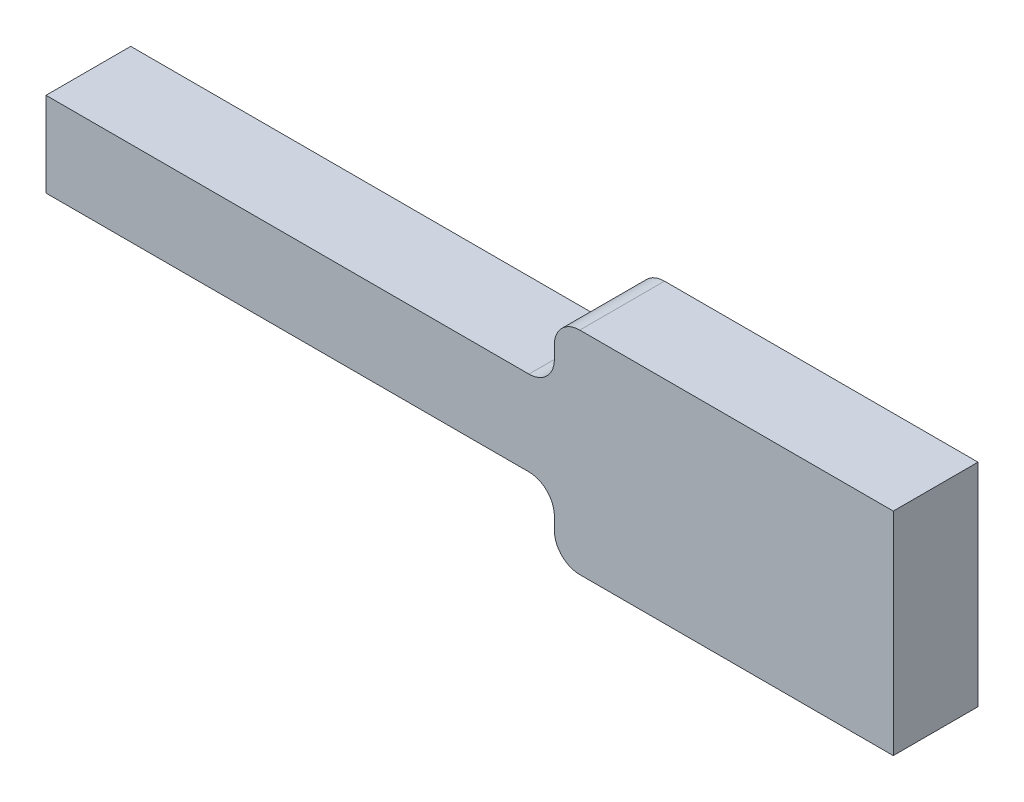
SolidWorks part; units mm, degrees
ref_plane "Front Plane" through (0, 0, 0) normal (0, 0, 1) x (1, 0, 0)
ref_plane "Top Plane" through (0, 0, 0) normal (0, 1, 0) x (1, 0, 0)
ref_plane "Right Plane" through (0, 0, 0) normal (1, 0, 0) x (0, 0, -1)
sketch "Sketch2" plane through (0, 0, 0) normal (0, 1, 0) x (1, 0, 0)
  line L1 (-50, -5) -> (50, -5)
  line L2 (-50, -5) -> (-50, 5)
  line L3 (-50, 5) -> (50, 5)
  line L4 (50, -5) -> (50, 5)
  line L5 (-50, -5) -> (50, 5) construction
  line L6 (-50, 5) -> (50, -5) construction
  point P0 (0, 0)
  dimension "D1" = 100
  dimension "D2" = 10
extrude "Boss-Extrude2" add sketch "Sketch2" along normal mid plane 25
sketch "Sketch6" plane through (0, 0, 5) normal (0, 0, 1) x (1, 0, 0)
  line L0 (226.9382, 0) -> (-226.9382, 0) construction
  line L1 (-50, 12.5) -> (10, 12.5)
  line L2 (-50, 12.5) -> (-50, 5)
  line L3 (-50, 5) -> (10, 5)
  line L4 (10, 12.5) -> (10, 5)
  line L5 (0, 0) -> (50000, 0) construction
  line L6 (10, -12.5) -> (10, -5)
  line L7 (-50, -12.5) -> (-50, -5)
  line L8 (-50, -12.5) -> (10, -12.5)
  line L9 (-50, -5) -> (10, -5)
  dimension "D1" = 5
  dimension "D2" = 60
extrude "Cut-Extrude3" cut sketch "Sketch6" against normal through all both and the other way through all
fillet "Fillet2" radius 3 4 edges at (10, 12.5, 0) (10, 5, 0) (10, -5, 0) (10, -12.5, 0)
